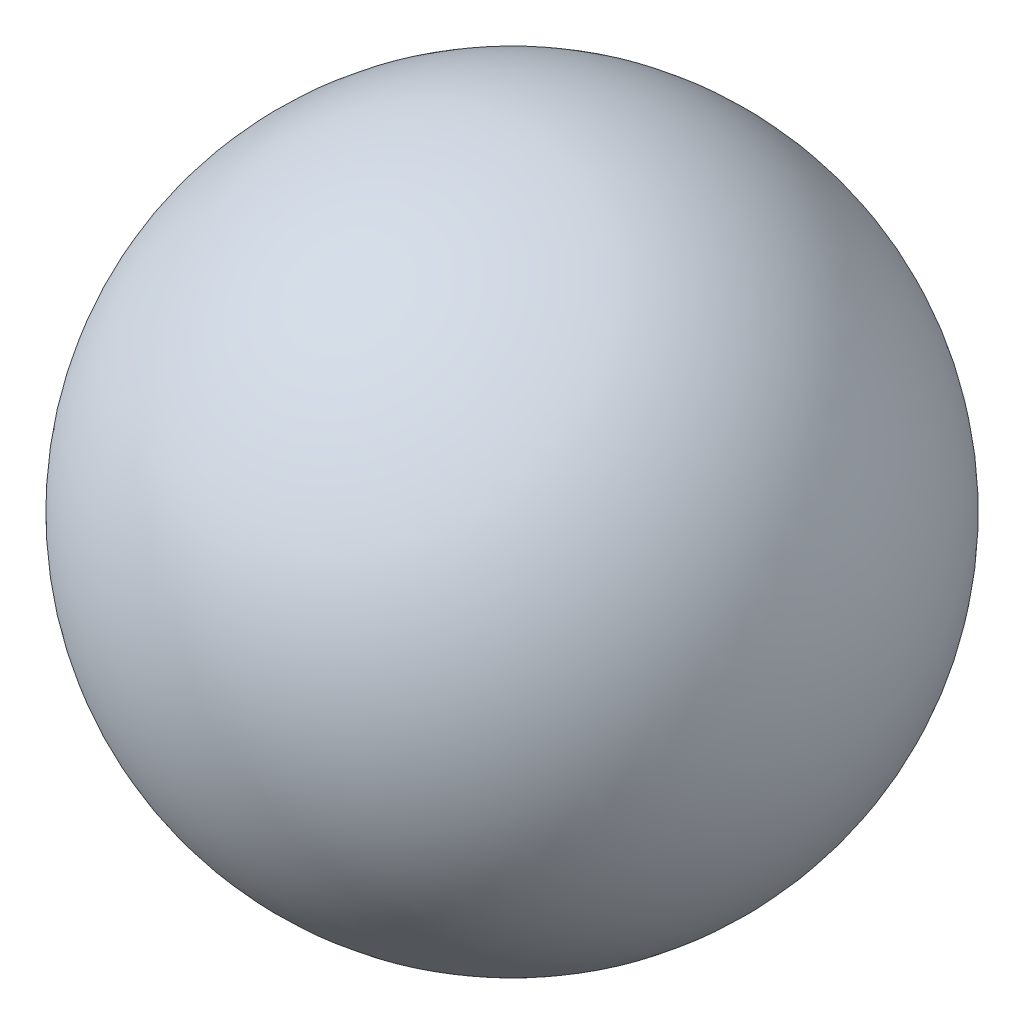
SolidWorks part; units mm, degrees
ref_plane "Front Plane" through (0, 0, 0) normal (0, 0, 1) x (1, 0, 0)
ref_plane "Top Plane" through (0, 0, 0) normal (0, 1, 0) x (1, 0, 0)
ref_plane "Right Plane" through (0, 0, 0) normal (1, 0, 0) x (0, 0, -1)
sketch "PingPongBallSketch" plane through (0, 0, 0) normal (0, 0, 1) x (1, 0, 0)
  line L0 (0, 20) -> (0, 19)
  line L1 (0, -19) -> (0, -20)
  line L2 (0, 15.0191) -> (0, -14.1352) construction
  arc A0 (0, 20) -> (0, -20) centre (0, 0) cw
  arc A1 (0, 19) -> (0, -19) centre (0, 0) cw
  dimension "D1" = 20
  dimension "D2" = 19
revolve "PingPongBall" add sketch "PingPongBallSketch" angle 360 about L2
ref_plane "Plane1" through (-20, 0, 0) normal (1, 0, 0) x (0, 0, -1)
